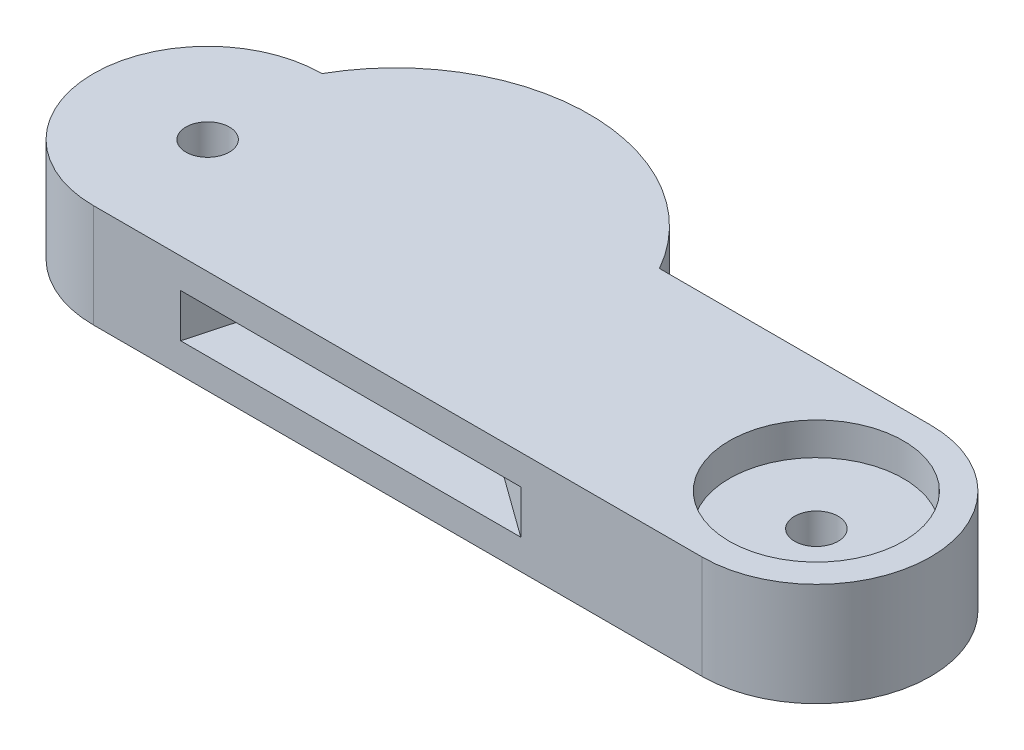
SolidWorks part; units mm, degrees
ref_plane "Front Plane" through (0, 0, 0) normal (0, 0, 1) x (1, 0, 0)
ref_plane "Top Plane" through (0, 0, 0) normal (0, 1, 0) x (1, 0, 0)
ref_plane "Right Plane" through (0, 0, 0) normal (1, 0, 0) x (0, 0, -1)
sketch "Sketch1" plane through (0, 0, 0) normal (0, 1, 0) x (1, 0, 0)
  line L0 (0, -10.5004) -> (-55.9305, -10.5004)
  line L1 (0, 10.5004) -> (-55.9305, 10.5004)
  line L5 (0, 11.5004) -> (-55.9305, 11.5004) construction
  line L6 (0, -11.5004) -> (-55.9305, -11.5004) construction
  circle A0 centre (0, 0) radius 2
  arc A1 (0, -10.5004) -> (0, 10.5004) centre (0, 0) ccw
  arc A2 (-55.9305, 10.5004) -> (-55.9305, -10.5004) centre (-55.9305, 0) ccw
  circle A3 centre (-55.9305, 0) radius 2
  arc A7 (0, -11.5004) -> (0, 11.5004) centre (0, 0) ccw construction
  arc A8 (-55.9305, 11.5004) -> (-55.9305, -11.5004) centre (-55.9305, 0) ccw construction
  arc A9 (-55.2376, -38.6748) -> (-39.2208, -41.4996) centre (-45.8168, -32.0788) ccw construction
  arc A10 (-55.9305, 10.5004) -> (-55.9305, -10.5004) centre (-55.9305, 0) ccw construction
  circle A11 centre (0, 0) radius 67.4309 construction
  arc A12 (-67.3132, -3.9833) -> (-55.2376, -38.6748) centre (0, 0) ccw construction
  dimension "D1" = 4
  dimension "D2" = 1
  dimension "D3" = 4
extrude "Boss-Extrude1" add sketch "Sketch1" along normal mid plane 9.5
sketch "Sketch3" plane through (0, 0, 0) normal (0, 1, 0) x (1, 0, 0)
  line L0 (0, 0) -> (-47.1525, -15.3208) construction
  line L1 (0, 0) -> (24.7895, -42.9367) construction
  line L2 (0, 0) -> (-55.9305, 0) construction
  line L3 (24.7895, -42.9367) -> (-41.5934, 5.0595) construction
  line L4 (-41.5934, 5.0595) -> (-47.1525, -15.3208) construction
  line L5 (-41.5934, 5.0595) -> (-37.6461, 19.5308) construction
  line L6 (-41.5934, 5.0595) -> (-53.749, 13.8482) construction
  line L7 (22.8477, -44.0007) -> (-38.0092, 0) construction
  line L8 (-35.7518, 18.8753) -> (-39.2995, 5.869)
  line L9 (-43.8873, 4.25) -> (-54.8123, 12.149)
  line L11 (26.6452, -41.8104) -> (-39.2995, 5.869)
  line L12 (-39.6108, 19.9279) -> (-42.7627, 8.3729) construction
  line L13 (-42.7627, 8.3729) -> (-52.4686, 15.3905) construction
  line L14 (-40.9004, 0) -> (-45.9674, -18.5763) construction
  line L15 (-43.8873, 4.25) -> (-48.2065, -11.585)
  line L18 (-40.4216, 6.6802) -> (-50.8477, 14.2185) construction
  line L20 (-41.5934, 5.0595) -> (-52.0196, 12.5978) construction
  line L21 (-42.7652, 3.4387) -> (-53.1914, 10.977) construction
  line L23 (-43.5229, 5.5858) -> (-49.082, -14.7945) construction
  line L26 (-39.6639, 4.5332) -> (-45.223, -15.8471) construction
  line L27 (25.9613, -41.316) -> (-40.4216, 6.6802) construction
  line L28 (23.6177, -44.5574) -> (-42.7652, 3.4387) construction
  arc A1 (-48.2065, -11.585) -> (26.6452, -41.8104) centre (0, 0) ccw
  arc A4 (-55.9305, 10.5004) -> (-55.9305, -10.5004) centre (-55.9305, 0) ccw construction
  arc A7 (-35.7518, 18.8753) -> (-54.8123, 12.149) centre (-41.5934, 5.0595) ccw
  dimension "D1" = 99.1581
  dimension "D3" = 120
  dimension "D6" = 30
  dimension "D2" = 18
  dimension "D4" = 2
  dimension "D5" = 2
extrude "Cut-Extrude1" cut sketch "Sketch3" against normal mid plane 4
sketch "Sketch5" plane through (0, 0, 0) normal (0, 1, 0) x (1, 0, 0)
  line L0 (-40.4241, 1.7461) -> (-52.5322, 10.5004) construction
  line L1 (-40.4241, 1.7461) -> (-35.7382, 18.9254) construction
  line L2 (-52.5322, 10.5004) -> (-43.8873, 4.25) construction
  line L3 (-39.2995, 5.869) -> (-38.0362, 10.5004) construction
  line L4 (-55.9305, 10.5004) -> (-24.9177, 10.5004)
  line L5 (0, 10.5004) -> (-55.9305, 10.5004) construction
  circle A0 centre (-40.4241, 1.7461) radius 17.807
extrude "Boss-Extrude2" add sketch "Sketch5" along normal up to surface and the other way up to surface
sketch "Sketch6" plane through (0, 0, 0) normal (0, 1, 0) x (1, 0, 0)
  line L0 (-39.2995, 5.869) -> (-16.6593, -10.5004)
  line L1 (-47.9107, -10.5004) -> (-43.8873, 4.25)
  line L2 (-43.8873, 4.25) -> (-54.8544, 12.1794)
  line L3 (-39.2995, 5.869) -> (-35.7382, 18.9254)
  line L4 (-16.6593, -10.5004) -> (-39.2995, 5.869) construction
  line L5 (-43.8873, 4.25) -> (-47.9107, -10.5004) construction
  line L6 (-52.5322, 10.5004) -> (-43.8873, 4.25) construction
  line L7 (-39.2995, 5.869) -> (-38.0362, 10.5004) construction
  line L8 (-55.9305, -10.5004) -> (0, -10.5004) construction
  line L9 (-16.6593, -10.5004) -> (-47.9107, -10.5004)
  arc A0 (-24.9177, 10.5004) -> (-55.9305, 10.5004) centre (-40.4241, 1.7461) ccw construction
  arc A1 (-35.7382, 18.9254) -> (-54.8544, 12.1794) centre (-40.4241, 1.7461) ccw
extrude "Cut-Extrude2" cut sketch "Sketch6" against normal mid plane 4
sketch "Sketch7" plane through (0, 4.75, 0) normal (0, 1, 0) x (1, 0, 0)
  circle A0 centre (0, 0) radius 8
  dimension "D1" = 16
extrude "Cut-Extrude3" cut sketch "Sketch7" against normal blind 3
ref_plane "Plane1" through (0, 0, 0) normal (0, 1, 0) x (1, 0, 0)
